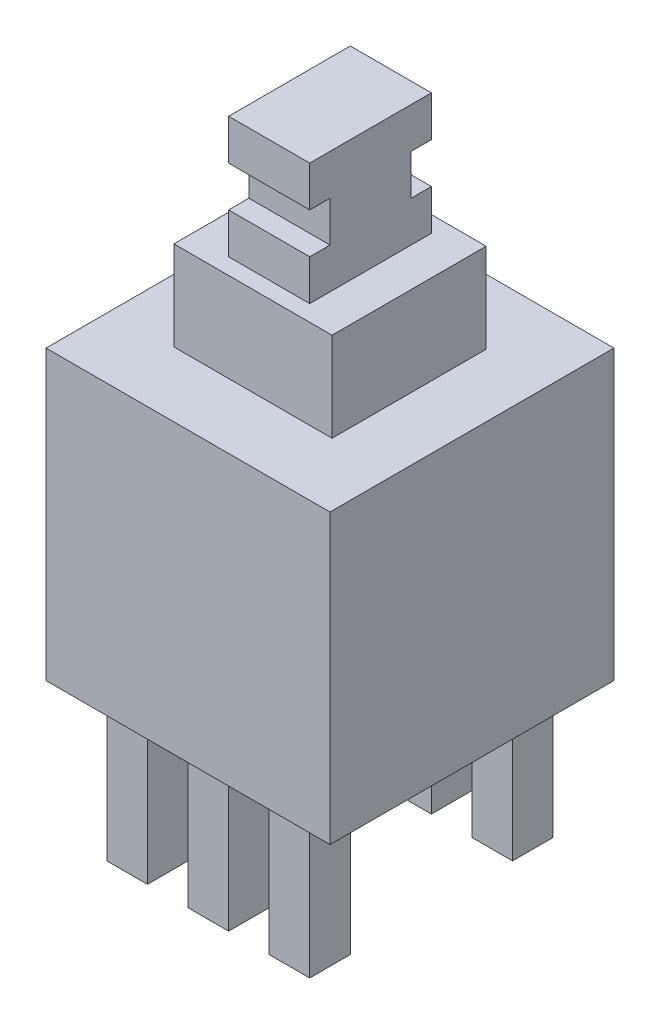
SolidWorks part; units mm, degrees
ref_plane "Front Plane" through (0, 0, 0) normal (0, 0, 1) x (1, 0, 0)
ref_plane "Top Plane" through (0, 0, 0) normal (0, 1, 0) x (1, 0, 0)
ref_plane "Right Plane" through (0, 0, 0) normal (1, 0, 0) x (0, 0, -1)
sketch "Sketch1" plane through (0, 0, 0) normal (0, 1, 0) x (1, 0, 0)
  line L1 (-3.5, -3.5) -> (3.5, -3.5)
  line L2 (-3.5, -3.5) -> (-3.5, 3.5)
  line L3 (-3.5, 3.5) -> (3.5, 3.5)
  line L4 (3.5, -3.5) -> (3.5, 3.5)
  line L5 (-3.5, -3.5) -> (3.5, 3.5) construction
  line L6 (-3.5, 3.5) -> (3.5, -3.5) construction
  point P0 (0, 0)
  dimension "D1" = 7
extrude "Boss-Extrude1" add sketch "Sketch1" along normal blind 7.1
sketch "Sketch2" plane through (0, 7.1, 0) normal (0, 1, 0) x (1, 0, 0)
  line L1 (-1.95, -1.9) -> (1.95, -1.9)
  line L2 (-1.95, -1.9) -> (-1.95, 1.9)
  line L3 (-1.95, 1.9) -> (1.95, 1.9)
  line L4 (1.95, -1.9) -> (1.95, 1.9)
  line L5 (-1.95, -1.9) -> (1.95, 1.9) construction
  line L6 (-1.95, 1.9) -> (1.95, -1.9) construction
  point P0 (0, 0)
  dimension "D1" = 3.9
  dimension "D2" = 3.8
extrude "Boss-Extrude2" add sketch "Sketch2" along normal blind 2.2
sketch "Sketch3" plane through (0, 9.3, 0) normal (0, 1, 0) x (1, 0, 0)
  line L1 (-1, -1.5) -> (1, -1.5)
  line L2 (-1, -1.5) -> (-1, 1.5)
  line L3 (-1, 1.5) -> (1, 1.5)
  line L4 (1, -1.5) -> (1, 1.5)
  line L5 (-1, -1.5) -> (1, 1.5) construction
  line L6 (-1, 1.5) -> (1, -1.5) construction
  point P0 (0, 0)
  dimension "D1" = 2
  dimension "D2" = 3
extrude "Boss-Extrude3" add sketch "Sketch3" along normal blind 3
sketch "Sketch4" plane through (0, 0, 0) normal (0, -1, 0) x (1, 0, 0)
  line L0 (-0.5, 3) -> (-0.5, 2)
  line L1 (-2.5, 3) -> (-1.5, 3)
  line L2 (-2.5, 3) -> (-2.5, 2)
  line L3 (-2.5, 2) -> (-1.5, 2)
  line L4 (-1.5, 3) -> (-1.5, 2)
  line L5 (-0.5, 3) -> (0.5, 3)
  line L6 (0.5, 3) -> (0.5, 2)
  line L7 (-0.5, 2) -> (0.5, 2)
  line L8 (1.5, 3) -> (1.5, 2)
  line L9 (1.5, 3) -> (2.5, 3)
  line L10 (2.5, 3) -> (2.5, 2)
  line L11 (1.5, 2) -> (2.5, 2)
  line L12 (-0.5, -2) -> (-0.5, -3)
  line L13 (-0.5, -2) -> (0.5, -2)
  line L14 (0.5, -2) -> (0.5, -3)
  line L15 (-0.5, -3) -> (0.5, -3)
  line L16 (1.5, -2) -> (1.5, -3)
  line L17 (1.5, -2) -> (2.5, -2)
  line L18 (2.5, -2) -> (2.5, -3)
  line L19 (1.5, -3) -> (2.5, -3)
  line L20 (-2.5, -2) -> (-2.5, -3)
  line L21 (-2.5, -2) -> (-1.5, -2)
  line L22 (-1.5, -2) -> (-1.5, -3)
  line L23 (-2.5, -3) -> (-1.5, -3)
  point P4 (-2, 2)
  point P6 (-2.5, 2.5)
  point P7 (2.5, -2.5)
  point P8 (2, -2)
  point P29 (2, 2)
  dimension "D1" = 2
  dimension "D2" = 1
  dimension "D3" = 1
  dimension "D4" = 2.5
  dimension "D7" = 2.5
  dimension "D8" = 2
  dimension "D9" = 2
  dimension "D5" = 3
  dimension "D6" = 2
extrude "Boss-Extrude4" add sketch "Sketch4" along normal blind 3.6
sketch "Sketch5" plane through (1, 0, 0) normal (1, 0, 0) x (0, 0, -1)
  line L0 (-1.5, 12.3) -> (-1.5, 9.3) construction
  line L1 (-1.5, 11.3) -> (-1, 11.3)
  line L2 (-1.5, 11.3) -> (-1.5, 10.3)
  line L3 (-1.5, 10.3) -> (-1, 10.3)
  line L4 (-1, 11.3) -> (-1, 10.3)
  line L5 (1.5, 12.3) -> (1.5, 9.3) construction
  line L6 (1.5, 11.3) -> (1, 11.3)
  line L7 (1.5, 11.3) -> (1.5, 10.3)
  line L8 (1.5, 10.3) -> (1, 10.3)
  line L9 (1, 11.3) -> (1, 10.3)
  line L10 (-1.5, 12.3) -> (1.5, 12.3) construction
  dimension "D1" = 0.5
  dimension "D2" = 1
  dimension "D3" = 1
extrude "Cut-Extrude1" cut sketch "Sketch5" against normal through all
ref_plane "MAX" through (0, 11.8, 0) normal (0, 1, 0) x (1, 0, 0)
ref_plane "MIN" through (0, 10.7, 0) normal (0, 1, 0) x (1, 0, 0)
equation "\"D7@Sketch4\"=\"D4@Sketch4\""
equation "\"D8@Sketch4\"=\"D1@Sketch4\""
equation "\"D9@Sketch4\"=\"D1@Sketch4\""
